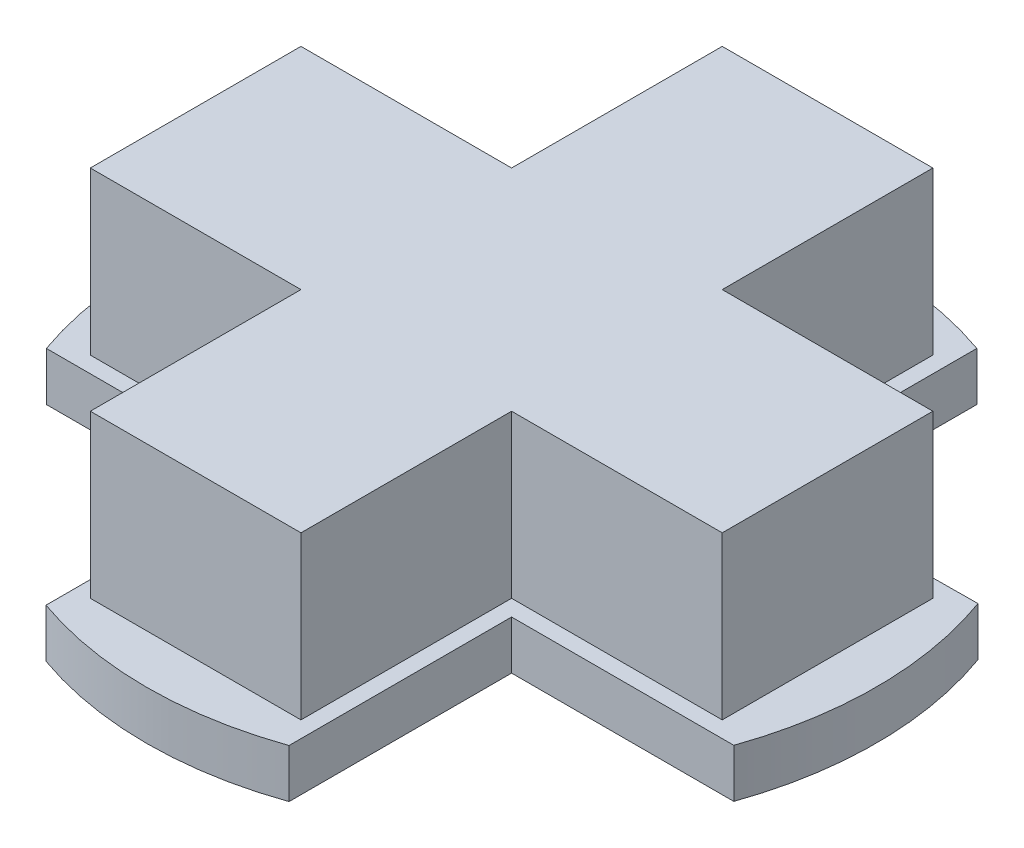
SolidWorks part; units mm, degrees
ref_plane "前视基准面" through (0, 0, 0) normal (0, 0, 1) x (1, 0, 0)
ref_plane "上视基准面" through (0, 0, 0) normal (0, 1, 0) x (1, 0, 0)
ref_plane "右视基准面" through (0, 0, 0) normal (1, 0, 0) x (0, 0, -1)
sketch "草图3" plane through (0, 0, 0) normal (0, 1, 0) x (1, 0, 0)
  line L12 (-12.7279, 4.5) -> (-4.5, 4.5)
  line L13 (-4.5, 4.5) -> (-4.5, 12.7279)
  line L14 (4.5, 12.7279) -> (4.5, 4.5)
  line L15 (4.5, 4.5) -> (12.7038, 4.5676)
  line L16 (12.7279, -4.5) -> (4.5, -4.5)
  line L17 (4.5, -4.5) -> (4.5, -12.7414)
  line L18 (-4.5, -12.7414) -> (-4.5, -4.5)
  line L19 (-4.5, -4.5) -> (-12.7279, -4.5)
  arc A1 (4.5, 12.7279) -> (-4.5, 12.7279) centre (0, 0) ccw
  arc A2 (-12.7279, 4.5) -> (-12.7279, -4.5) centre (0, 0) ccw
  arc A3 (-4.5, -12.7414) -> (4.5, -12.7414) centre (0, 0) ccw
  arc A4 (12.7279, -4.5) -> (12.7038, 4.5676) centre (0, 0) ccw
extrude "凸台-拉伸2" add sketch "草图3" along normal blind 1.8 contours L12 L13 A1 L14 L15 A4 L16 L17 A3 L18 L19 A2
sketch "草图4" plane through (0, 1.8, 0) normal (0, 1, 0) x (1, 0, 0)
  line L2 (3.9, -11.7) -> (-3.9, -11.7)
  line L4 (-3.9, 11.7) -> (3.9, 11.7)
  line L8 (11.7, 3.9) -> (11.7, -3.9)
  line L10 (-11.7, -3.9) -> (-11.7, 3.9)
  line L12 (-3.9, 11.7) -> (-3.9, 3.9)
  line L13 (-3.9, 3.9) -> (-11.7, 3.9)
  line L14 (-11.7, -3.9) -> (-3.9, -3.9)
  line L15 (-3.9, -3.9) -> (-3.9, -11.7)
  line L16 (3.9, -11.7) -> (3.9, -3.9)
  line L17 (3.9, -3.9) -> (11.7, -3.9)
  line L18 (11.7, 3.9) -> (3.9, 3.9)
  line L19 (3.9, 3.9) -> (3.9, 11.7)
extrude "凸台-拉伸3" add sketch "草图4" along normal blind 6
